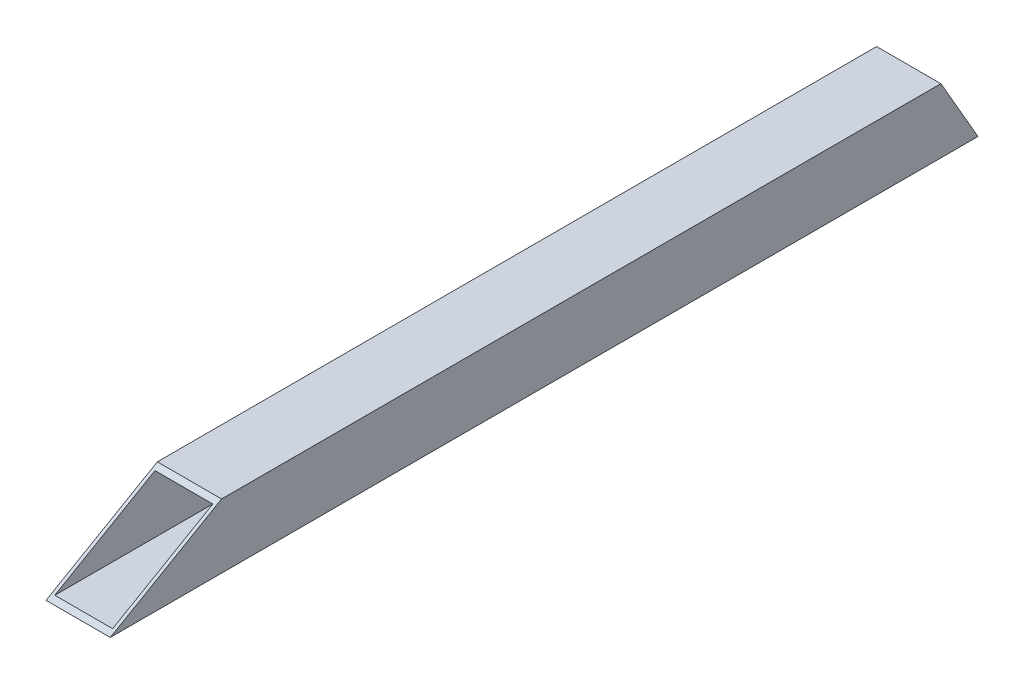
SolidWorks part; units mm, degrees
ref_plane "前视基准面" through (0, 0, 0) normal (0, 0, 1) x (1, 0, 0)
ref_plane "上视基准面" through (0, 0, 0) normal (0, 1, 0) x (1, 0, 0)
ref_plane "右视基准面" through (0, 0, 0) normal (1, 0, 0) x (0, 0, -1)
other "Configuration Table"
sketch "草图1" plane through (0, 0, 0) normal (0, 0, 1) x (1, 0, 0)
  line L1 (0, 0) -> (20, 0)
  line L2 (0, 0) -> (0, 20)
  line L3 (0, 20) -> (20, 20)
  line L4 (20, 0) -> (20, 20)
  line L5 (1, 1) -> (19, 1)
  line L6 (1, 1) -> (1, 19)
  line L7 (1, 19) -> (19, 19)
  line L8 (19, 1) -> (19, 19)
  dimension "D1" = 20
  dimension "D2" = 20
  dimension "D3" = 1
  dimension "D4" = 1
  dimension "D5" = 1
  dimension "D6" = 1
extrude "凸台-拉伸1" add sketch "草图1" along normal blind 270
sketch "草图2" plane through (20, 0, 0) normal (1, 0, 0) x (0, 0, -1)
  line L0 (-270, 20) -> (-270, 0)
  line L1 (-270, 0) -> (-235.359, 20)
  line L2 (-270, 20) -> (0, 20) construction
  line L3 (-235.359, 20) -> (-270, 20)
  line L4 (-11.547, 20) -> (0, 20)
  line L5 (0, 20) -> (0, 0)
  line L6 (0, 0) -> (-11.547, 20)
  point P10 (-217.0264, 20)
  dimension "D1" = 60
extrude "切除-拉伸1" cut sketch "草图2" against normal blind 250
